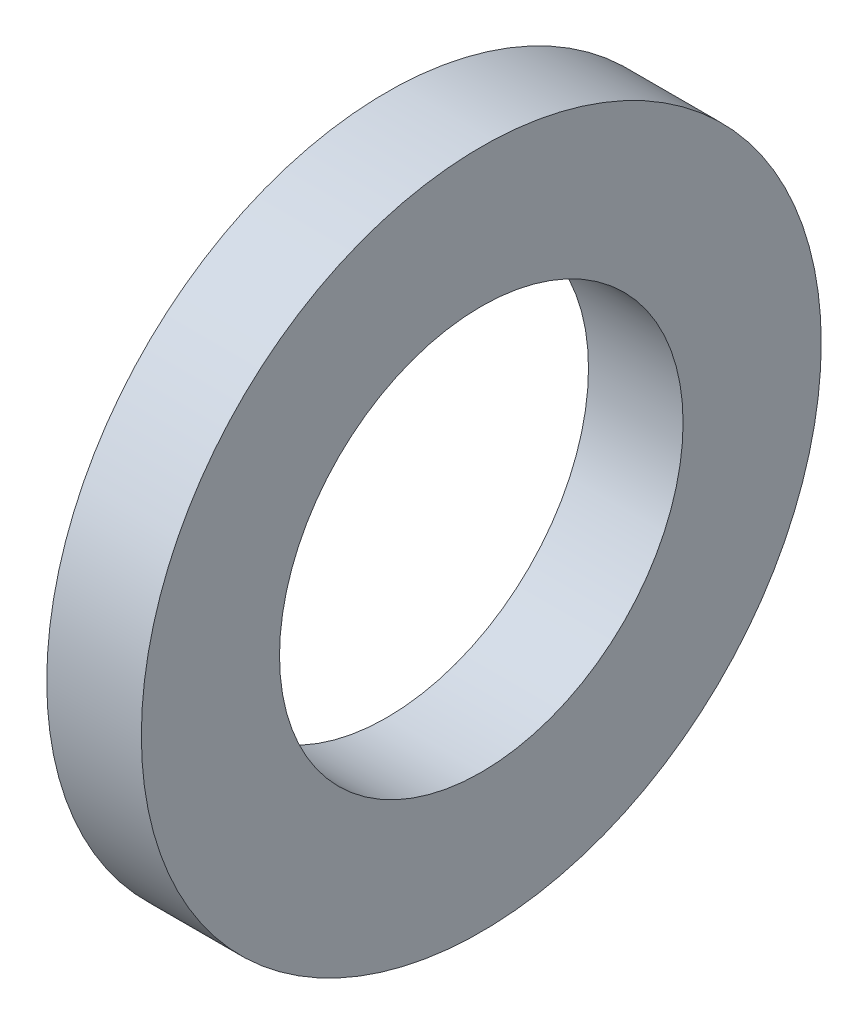
SolidWorks part; units mm, degrees
ref_plane "Front Plane" through (0, 0, 0) normal (0, 0, 1) x (1, 0, 0)
ref_plane "Top Plane" through (0, 0, 0) normal (0, 1, 0) x (1, 0, 0)
ref_plane "Right Plane" through (0, 0, 0) normal (1, 0, 0) x (0, 0, -1)
sketch "Sketch1" plane through (0, 0, 0) normal (1, 0, 0) x (0, 0, -1)
  circle A0 centre (0, 0) radius 27.305
  circle A1 centre (0, 0) radius 46
  dimension "D1" = 54.61
  dimension "D2" = 92
extrude "Boss-Extrude1" add sketch "Sketch1" along normal blind 12.8
